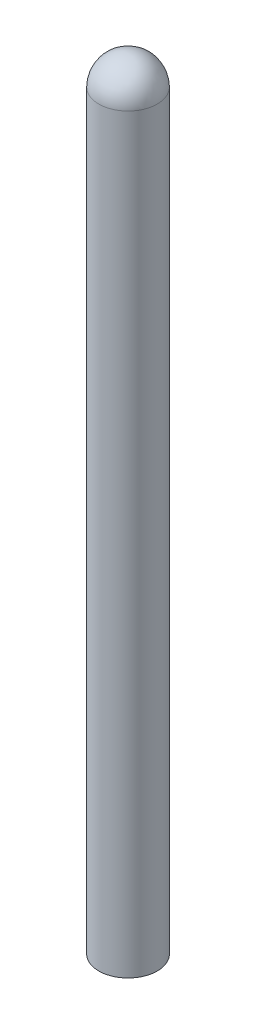
SolidWorks part; units mm, degrees
ref_plane "Front Plane" through (0, 0, 0) normal (0, 0, 1) x (1, 0, 0)
ref_plane "Top Plane" through (0, 0, 0) normal (0, 1, 0) x (1, 0, 0)
ref_plane "Right Plane" through (0, 0, 0) normal (1, 0, 0) x (0, 0, -1)
sketch "Sketch1" plane through (0, 0, 0) normal (0, 1, 0) x (1, 0, 0)
  circle A0 centre (0, 0) radius 2.3812
  dimension "D1" = 4.7625
extrude "Extrude1" add sketch "Sketch1" along normal blind 63.5
fillet "Fillet1" radius 2.3813 1 edges at (0, 63.5, 2.3812)
